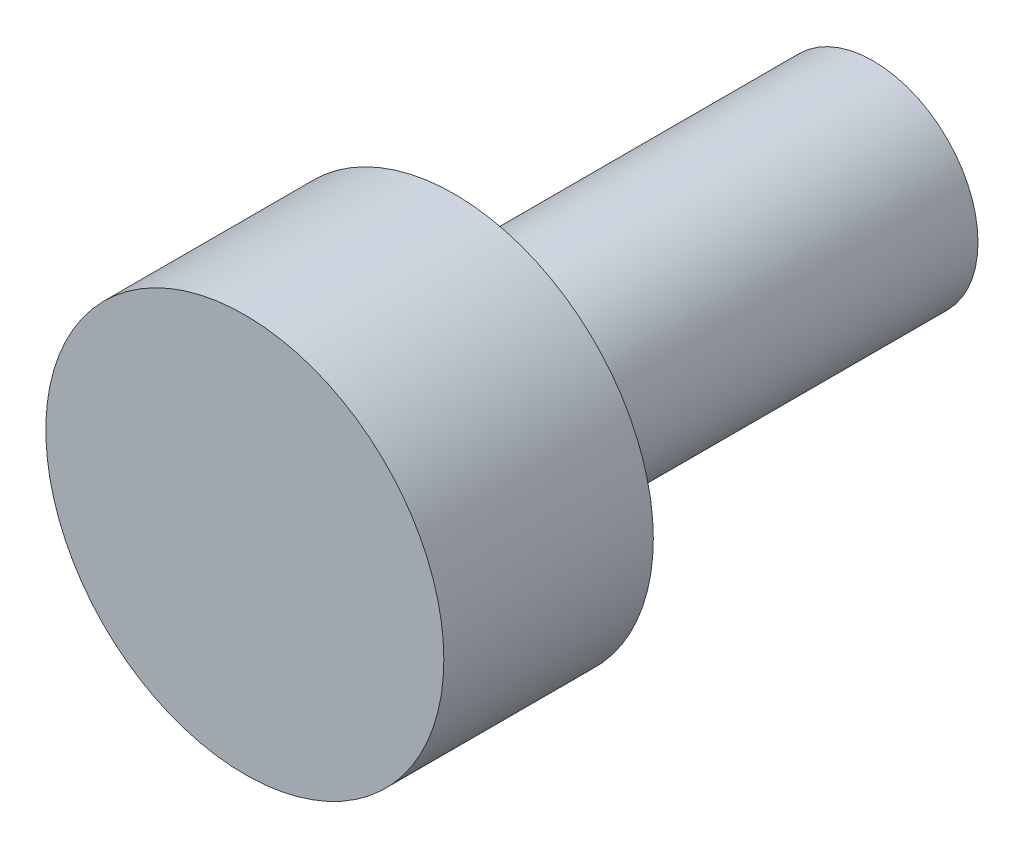
SolidWorks part; units mm, degrees
ref_plane "Front Plane" through (0, 0, 0) normal (0, 0, 1) x (1, 0, 0)
ref_plane "Top Plane" through (0, 0, 0) normal (0, 1, 0) x (1, 0, 0)
ref_plane "Right Plane" through (0, 0, 0) normal (1, 0, 0) x (0, 0, -1)
sketch "Sketch1" plane through (0, 0, 0) normal (0, 0, 1) x (1, 0, 0)
  circle A0 centre (0, 0) radius 1
extrude "Thread_Envelope" add sketch "Sketch1" along normal blind 4 from offset 4
sketch "Sketch2" plane through (0, 0, 0) normal (0, 0, 1) x (1, 0, 0)
  circle A0 centre (0, 0) radius 1.9
extrude "Head_Envelope" add sketch "Sketch2" along normal blind 2
